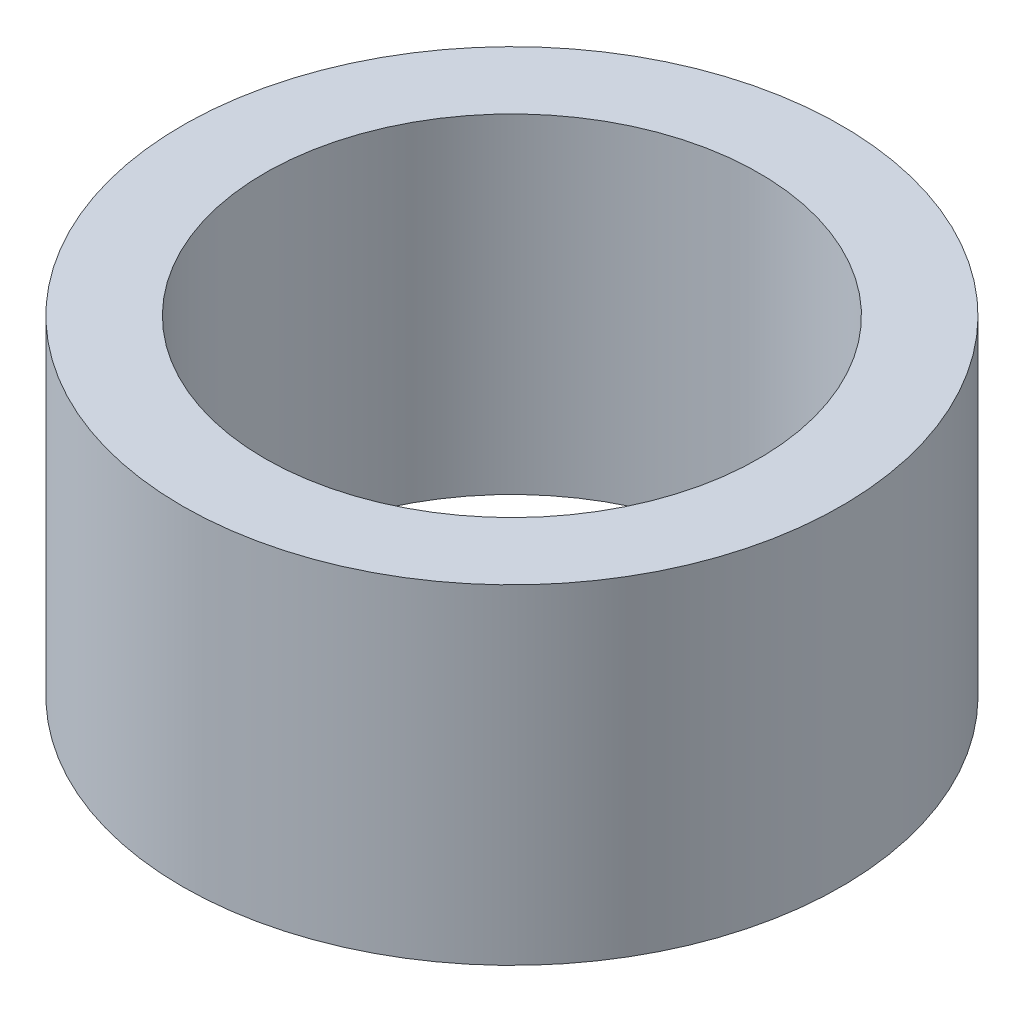
SolidWorks part; units mm, degrees
ref_plane "Front" through (0, 0, 0) normal (0, 0, 1) x (1, 0, 0)
ref_plane "Top" through (0, 0, 0) normal (0, 1, 0) x (1, 0, 0)
ref_plane "Right" through (0, 0, 0) normal (1, 0, 0) x (0, 0, -1)
sketch "Sketch1" plane through (0, 0, 0) normal (0, 1, 0) x (1, 0, 0)
  circle A0 centre (0, 0) radius 3
  circle A1 centre (0, 0) radius 4
extrude "Boss-Extrude1" add sketch "Sketch1" along normal blind 4
